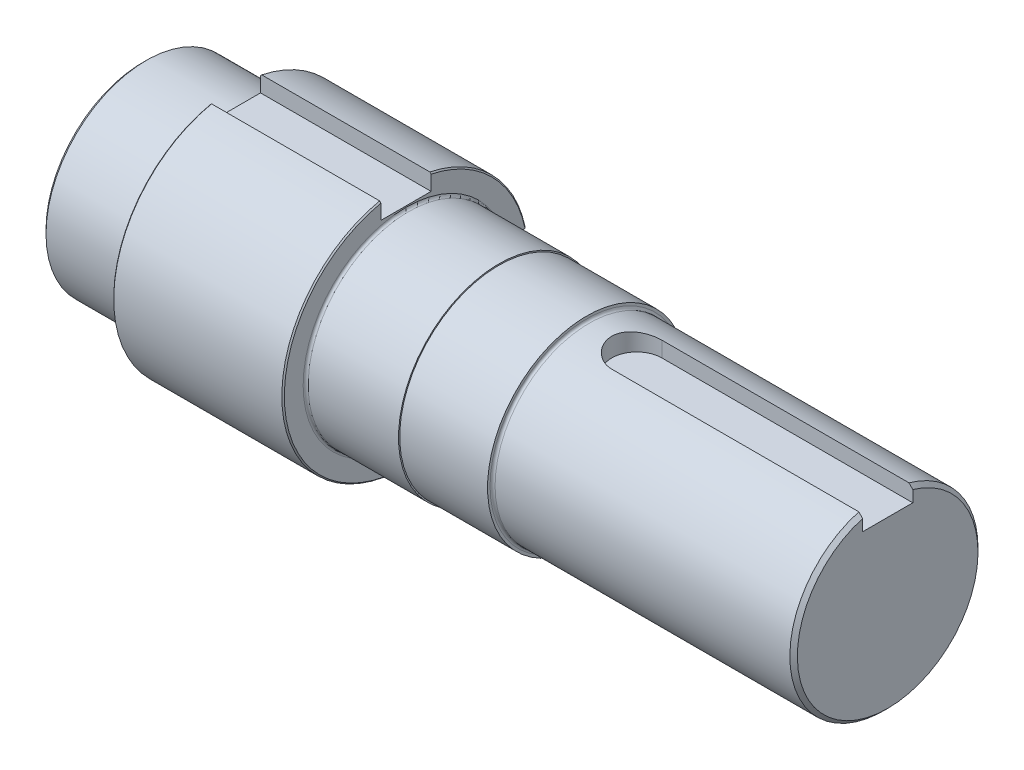
SolidWorks part; units mm, degrees
material "AISI 1020"
ref_plane "Front" through (0, 0, 0) normal (0, 0, 1) x (1, 0, 0)
ref_plane "Top" through (0, 0, 0) normal (0, 1, 0) x (1, 0, 0)
ref_plane "Right" through (0, 0, 0) normal (1, 0, 0) x (0, 0, -1)
sketch "Sketch1" plane through (0, 0, 0) normal (0, 0, 1) x (1, 0, 0)
  line L0 (0, 0) -> (-118.0576, 0) construction
  line L1 (0, 0) -> (297, 0)
  line L2 (297, 0) -> (297, 37.5)
  line L3 (297, 37.5) -> (177, 37.5)
  line L4 (177, 37.5) -> (177, 39.5)
  line L5 (177, 39.5) -> (142, 39.5)
  line L6 (142, 39.5) -> (142, 40)
  line L7 (142, 40) -> (105, 40)
  line L8 (0, 40) -> (0, 0)
  line L9 (105, 40) -> (105, 49)
  line L10 (105, 49) -> (37, 49)
  line L11 (37, 49) -> (37, 40)
  line L12 (37, 40) -> (0, 40)
  dimension "D1" = 75
  dimension "D2" = 120
  dimension "D3" = 79
  dimension "D4" = 80
  dimension "D5" = 35
  dimension "D6" = 37
  dimension "D7" = 37
  dimension "D8" = 68
  dimension "D9" = 98
revolve "Revolve1" add sketch "Sketch1" angle 360 about L0
sketch "Sketch2" plane through (37, 0, 0) normal (-1, 0, 0) x (0, 0, 1)
  line L0 (-10, 47.9687) -> (-10, 41.5)
  line L1 (-10, 41.5) -> (10, 41.5)
  line L2 (10, 41.5) -> (10, 47.9687)
  line L3 (-47.9687, 10) -> (-41.5, 10)
  line L4 (-41.5, 10) -> (-41.5, -10)
  line L5 (-41.5, -10) -> (-47.9687, -10)
  line L6 (-49, 0) -> (-41.5, 0) construction
  circle A0 centre (0, 0) radius 49 construction
  arc A1 (10, 47.9687) -> (-10, 47.9687) centre (0, 0) ccw
  arc A2 (-47.9687, 10) -> (-47.9687, -10) centre (0, 0) ccw
  dimension "D1" = 20
  dimension "D2" = 7.5
extrude "Extrude1" cut sketch "Sketch2" against normal up to surface (68 mm away) up to face at (105, 0, -49)
fillet "Fillet1" radius 1 3 edges at (177, 0, -37.5) (105, 0, -40) (37, 0, -40)
ref_plane "Plane1" through (237.5, 37.5, 0) normal (0, 1, 0) x (0, 0, 1)
sketch "Sketch3" plane through (237.5, 37.5, 0) normal (0, 1, 0) x (0, 0, 1)
  line L0 (0, 59.5) -> (0, -40.5) construction
  line L1 (37.5, 59.5) -> (-37.5, 59.5) construction
  line L2 (-10, 59.5) -> (-10, -40.5)
  line L3 (10, 59.5) -> (10, -40.5)
  arc A0 (-10, 59.5) -> (10, 59.5) centre (0, 59.5) cw
  arc A1 (-10, -40.5) -> (10, -40.5) centre (0, -40.5) ccw
  dimension "D3" = 100
  dimension "D1" = 10
  dimension "D2" = 10
extrude "Extrude2" cut sketch "Sketch3" against normal blind 7.5
chamfer "Chamfer1" distance 1.5 angle 45 2 edges at (297, -37.5, 0) (0, 0, -40)
chamfer "Chamfer2" distance 0.5 angle 45 4 edges at (37, -34.6482, 34.6482) (105, -34.6482, 34.6482) (105, 34.6482, -34.6482) (37, 34.6482, -34.6482)
sketch "Esboço1" [suppressed] plane through (297, 0, 0) normal (1, 0, 0) x (0, 0, -1)
  circle A0 centre (0, 0) radius 50.8
  dimension "D1" = 101.6
extrude "Extrusão1" [suppressed] add sketch "Esboço1" against normal blind 302
